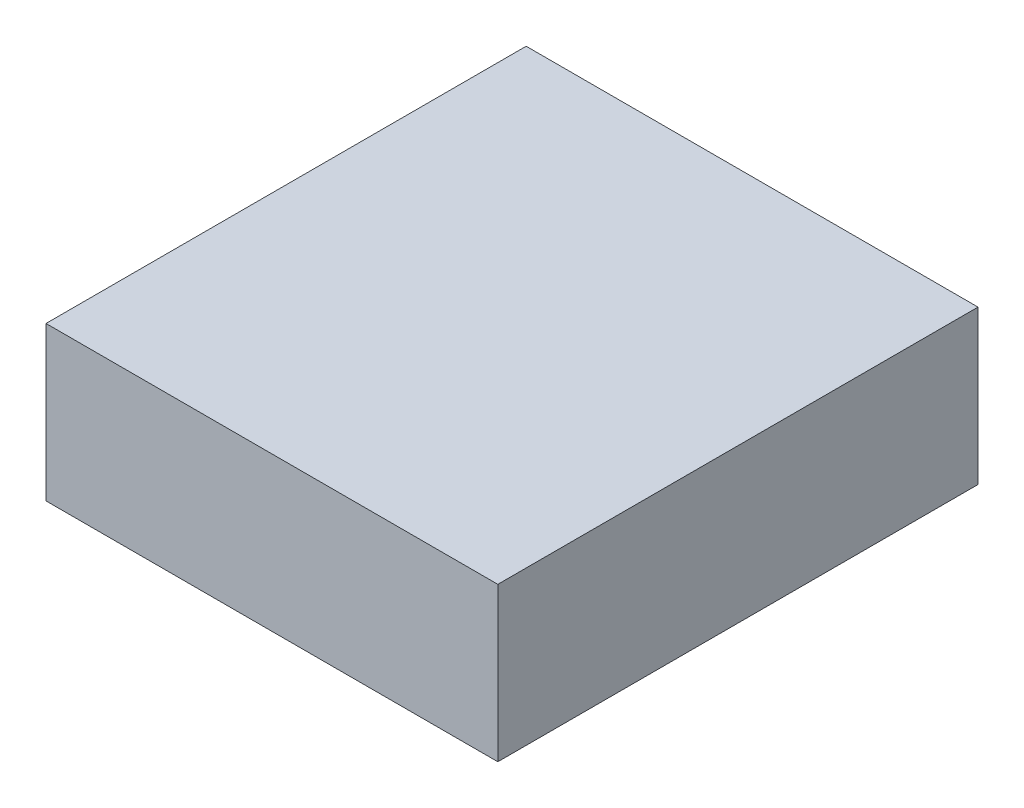
SolidWorks part; units mm, degrees
ref_plane "Front Plane" through (0, 0, 0) normal (0, 0, 1) x (1, 0, 0)
ref_plane "Top Plane" through (0, 0, 0) normal (0, 1, 0) x (1, 0, 0)
ref_plane "Right Plane" through (0, 0, 0) normal (1, 0, 0) x (0, 0, -1)
sketch "Sketch1" plane through (0, 0, 0) normal (0, 1, 0) x (1, 0, 0)
  line L1 (-45.085, -47.915) -> (45.085, -47.915)
  line L2 (-45.085, -47.915) -> (-45.085, 47.915)
  line L3 (-45.085, 47.915) -> (45.085, 47.915)
  line L4 (45.085, -47.915) -> (45.085, 47.915)
  line L5 (-45.085, -47.915) -> (45.085, 47.915) construction
  line L6 (-45.085, 47.915) -> (45.085, -47.915) construction
  point P0 (0, 0)
  dimension "D1" = 90.17
  dimension "D2" = 95.83
extrude "Boss-Extrude1" add sketch "Sketch1" along normal blind 30.67
